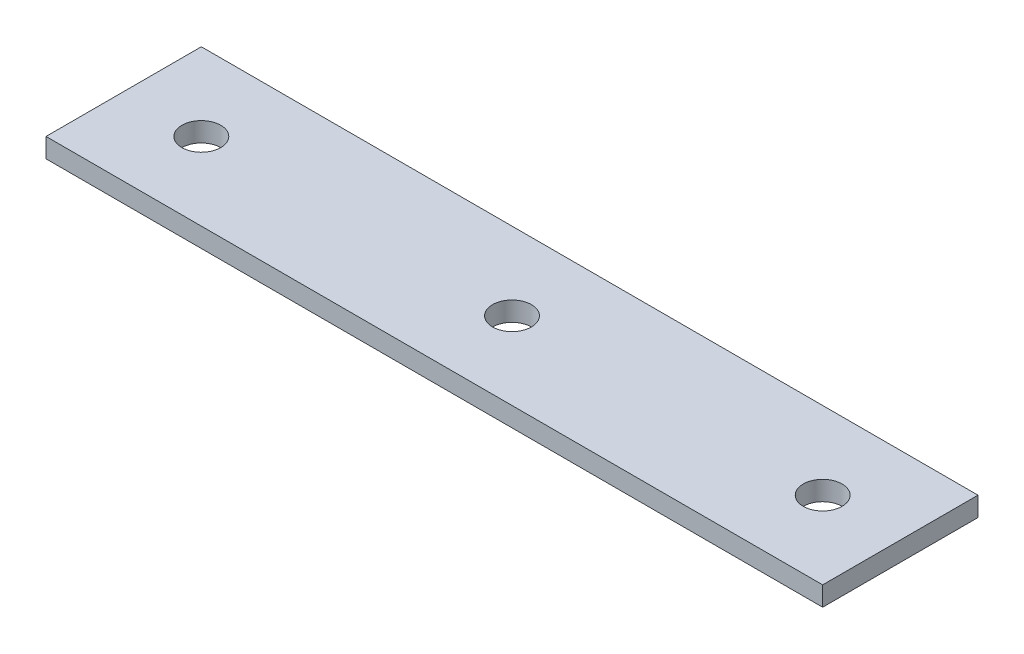
SolidWorks part; units mm, degrees
material "6061 Alloy"
ref_plane "Front Plane" through (0, 0, 0) normal (0, 0, 1) x (1, 0, 0)
ref_plane "Top Plane" through (0, 0, 0) normal (0, 1, 0) x (1, 0, 0)
ref_plane "Right Plane" through (0, 0, 0) normal (1, 0, 0) x (0, 0, -1)
sketch "Sketch1" plane through (0, 0, 0) normal (0, 1, 0) x (1, 0, 0)
  line L1 (0, 0) -> (127, 0)
  line L2 (0, 0) -> (0, 25.4)
  line L3 (0, 25.4) -> (127, 25.4)
  line L4 (127, 0) -> (127, 25.4)
  dimension "D1" = 25.4
  dimension "D2" = 127
extrude "Boss-Extrude1" add sketch "Sketch1" along normal blind 3.175 contours L3 L4 L1 L2
sketch "Sketch2" plane through (0, 3.175, 0) normal (0, 1, 0) x (1, 0, 0)
  line L0 (0, 25.4) -> (127, 25.4) construction
  line L1 (0, 0) -> (0, 25.4) construction
  line L2 (0, 0) -> (127, 0) construction
  line L3 (0, 0) -> (0, 25.4) construction
  circle A0 centre (12.7, 12.7) radius 3.175
  circle A1 centre (114.3, 12.7) radius 3.175
  circle A2 centre (63.5, 12.7) radius 3.175
  dimension "D1" = 6.35
  dimension "D2" = 12.7
  dimension "D3" = 12.7
  dimension "D4" = 12.7
  dimension "D5" = 114.3
  dimension "D6" = 12.7
  dimension "D7" = 63.5
extrude "Cut-Extrude1" cut sketch "Sketch2" against normal blind 3.175
